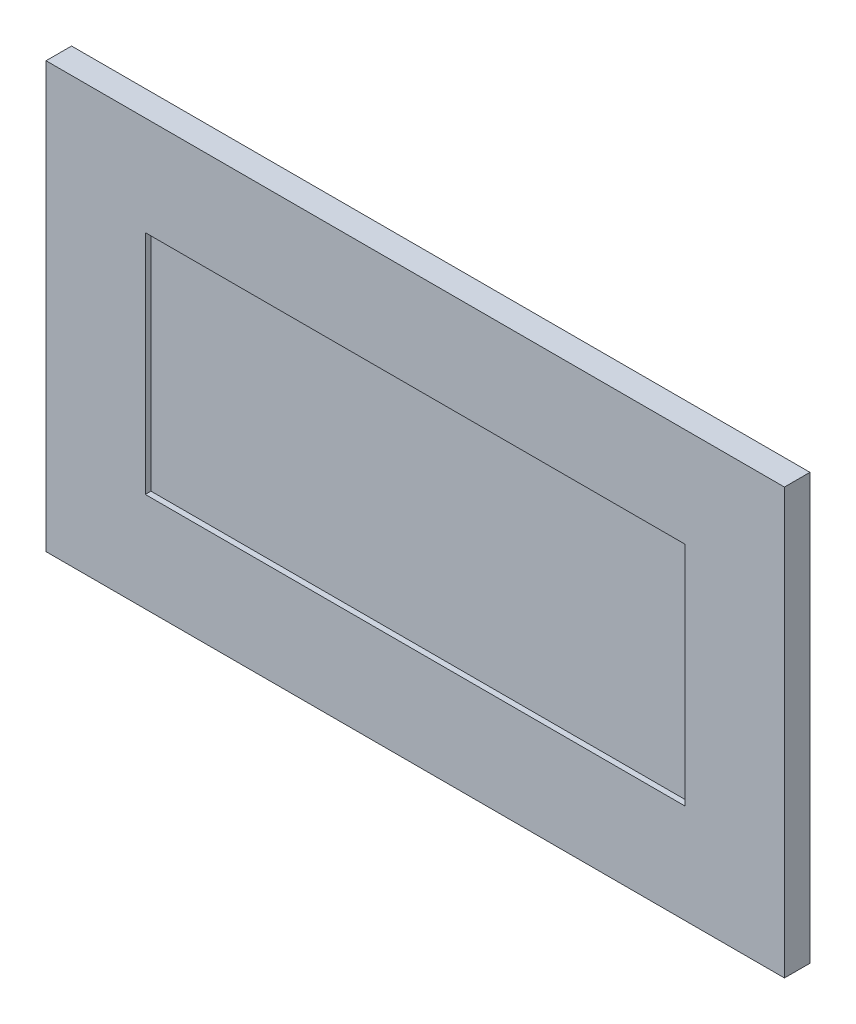
SolidWorks part; units mm, degrees
material "Pine"
ref_plane "Front Plane" through (0, 0, 0) normal (0, 0, 1) x (1, 0, 0)
ref_plane "Top Plane" through (0, 0, 0) normal (0, 1, 0) x (1, 0, 0)
ref_plane "Right Plane" through (0, 0, 0) normal (1, 0, 0) x (0, 0, -1)
sketch "Sketch1" plane through (0, 0, 0) normal (0, 0, 1) x (1, 0, 0)
  line L1 (-260.5, 150) -> (260.5, 150)
  line L2 (-260.5, 150) -> (-260.5, -150)
  line L3 (-260.5, -150) -> (260.5, -150)
  line L4 (260.5, 150) -> (260.5, -150)
  line L5 (-260.5, 150) -> (260.5, -150) construction
  line L6 (-260.5, -150) -> (260.5, 150) construction
  point P0 (0, 0)
  dimension "D1" = 300
  dimension "D2" = 521
extrude "Boss-Extrude1" add sketch "Sketch1" along normal blind 18
sketch "Sketch2" plane through (0, 0, 18) normal (0, 0, 1) x (1, 0, 0)
  line L0 (-260.5, 150) -> (-260.5, -150) construction
  line L1 (-190.5, 80) -> (190.5, 80)
  line L2 (-190.5, 80) -> (-190.5, -80)
  line L3 (-190.5, -80) -> (190.5, -80)
  line L4 (190.5, 80) -> (190.5, -80)
  line L5 (-190.5, 80) -> (190.5, -80) construction
  line L6 (-190.5, -80) -> (190.5, 80) construction
  line L7 (260.5, 150) -> (-260.5, 150) construction
  point P0 (0, 0)
  dimension "D1" = 70
  dimension "D2" = 70
extrude "Cut-Extrude1" cut sketch "Sketch2" against normal blind 4
